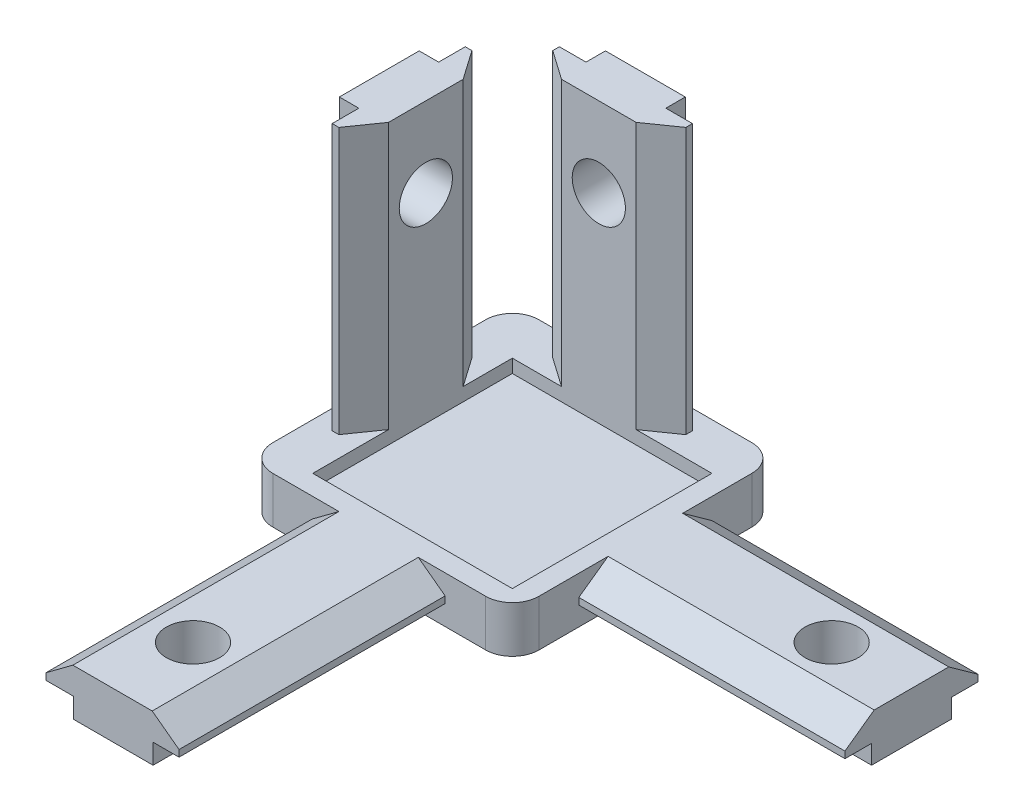
SolidWorks part; units mm, degrees
material "6063-T1"
ref_plane "Front Plane" through (0, 0, 0) normal (0, 0, 1) x (1, 0, 0)
ref_plane "Top Plane" through (0, 0, 0) normal (0, 1, 0) x (1, 0, 0)
ref_plane "Right Plane" through (0, 0, 0) normal (1, 0, 0) x (0, 0, -1)
sketch "Sketch1" plane through (0, 0, 0) normal (0, 1, 0) x (1, 0, 0)
  line L1 (8, -10) -> (-8, -10)
  line L2 (10, -8) -> (10, 8)
  line L3 (8, 10) -> (-8, 10)
  line L4 (-10, -8) -> (-10, 8)
  line L5 (10, -10) -> (-10, 10) construction
  line L6 (10, 10) -> (-10, -10) construction
  arc A0 (-10, -8) -> (-8, -10) centre (-8, -8) ccw
  arc A1 (8, -10) -> (10, -8) centre (8, -8) ccw
  arc A2 (10, 8) -> (8, 10) centre (8, 8) ccw
  arc A3 (-10, 8) -> (-8, 10) centre (-8, 8) cw
  point P0 (0, 0)
  dimension "D3" = 2
  dimension "D1" = 20
  dimension "D2" = 20
extrude "Boss-Extrude1" add sketch "Sketch1" along normal blind 3.5
sketch "Sketch2" plane through (0, 3.5, 0) normal (0, 1, 0) x (1, 0, 0)
  line L0 (-6.5, 6.5) -> (8.5, 6.5)
  line L1 (8.5, 6.5) -> (8.5, -8.5)
  line L2 (8.5, -8.5) -> (-6.5, -8.5)
  line L3 (-6.5, -8.5) -> (-6.5, 6.5)
  line L4 (-6.5, 2.965) -> (-10, 2.965) construction
  line L5 (-10, 8) -> (-10, -8) construction
  line L6 (1.2769, 6.5) -> (1.2769, 10) construction
  line L7 (8, 10) -> (-8, 10) construction
  dimension "D1" = 3.5
  dimension "D2" = 15
extrude "Cut-Extrude1" cut sketch "Sketch2" against normal blind 1
sketch "Sketch3" plane through (0, 3.5, 0) normal (0, 1, 0) x (1, 0, 0)
  line L0 (0, 10) -> (0, 6.5) construction
  line L1 (8, 10) -> (-8, 10) construction
  line L2 (8.5, 6.5) -> (-6.5, 6.5) construction
  line L3 (2.8032, 6.5) -> (-2.8032, 6.5)
  line L4 (8.5, 6.5) -> (-6.5, 6.5) construction
  line L5 (-2.8032, 6.5) -> (-5, 8.0375)
  line L7 (-3, 8.5375) -> (-3, 10)
  line L8 (-3, 10) -> (3, 10)
  line L9 (2.8032, 6.5) -> (5, 8.0375)
  line L11 (3, 8.5375) -> (3, 10)
  line L12 (-5, 8.0375) -> (-5, 8.5375)
  line L13 (-5, 8.5375) -> (-3, 8.5375)
  line L14 (5, 8.5375) -> (3, 8.5375)
  line L15 (5, 8.5375) -> (5, 8.0375)
  line L16 (-8.5375, 5) -> (-8.0375, 5)
  line L17 (-6.5, 2.8032) -> (-8.0375, 5)
  line L18 (-6.5, 2.8032) -> (-6.5, -2.8032)
  line L19 (-6.5, -2.8032) -> (-8.0375, -5)
  line L20 (-8.0375, -5) -> (-8.5375, -5)
  line L21 (-8.5375, -5) -> (-8.5375, -3)
  line L22 (-8.5375, -3) -> (-10, -3)
  line L23 (-10, -3) -> (-10, 3)
  line L24 (-8.5375, 3) -> (-10, 3)
  line L25 (-8.5375, 5) -> (-8.5375, 3)
  point P32 (0, 0)
  dimension "D1" = 3
  dimension "D2" = 10
  dimension "D3" = 0.5
  dimension "D4" = 2
extrude "Boss-Extrude2" add sketch "Sketch3" along normal blind 20
sketch "Sketch4" plane through (0, 0, 10) normal (0, 0, 1) x (1, 0, 0)
  line L0 (-8, 0) -> (8, 0) construction
  line L14 (2.9327, 3.5) -> (4.9508, 2)
  line L15 (4.9508, 1.5) -> (4.9508, 2)
  line L16 (4.9508, 1.5) -> (3, 1.5)
  line L17 (3, 1.5) -> (3, 0)
  line L18 (-3, 0) -> (3, 0)
  line L19 (-3, 1.5) -> (-3, 0)
  line L20 (-5.0492, 1.5) -> (-3, 1.5)
  line L21 (-5.0492, 2) -> (-5.0492, 1.5)
  line L22 (-3.0311, 3.5) -> (-5.0492, 2)
  line L23 (2.9327, 3.5) -> (-3.0311, 3.5)
  point P3 (0, 0)
  dimension "D1" = 10
  dimension "D2" = 6
  dimension "D3" = 3.5
  dimension "D4" = 1.5
  dimension "D5" = 0.5
extrude "Boss-Extrude3" add sketch "Sketch4" along normal blind 20
sketch "Sketch5" plane through (10, 0, 0) normal (1, 0, 0) x (0, 0, -1)
  line L0 (-8, 3.5) -> (8, 3.5) construction
  line L12 (2.8032, 3.5) -> (5, 1.9252)
  line L13 (5, 1.4252) -> (5, 1.9252)
  line L14 (5, 1.4252) -> (3, 1.4252)
  line L15 (3, 1.4252) -> (3, 0)
  line L16 (-3, 0) -> (3, 0)
  line L17 (-3, 1.4252) -> (-3, 0)
  line L18 (-5, 1.4252) -> (-3, 1.4252)
  line L19 (-5, 1.9252) -> (-5, 1.4252)
  line L20 (-2.8032, 3.5) -> (-5, 1.9252)
  line L21 (2.8032, 3.5) -> (-2.8032, 3.5)
  point P2 (0, 3.5)
  point P3 (0, 3.5)
  dimension "D1" = 10
  dimension "D2" = 1.4252
  dimension "D3" = 6
  dimension "D4" = 5.6065
  dimension "D5" = 3.5
extrude "Boss-Extrude4" add sketch "Sketch5" along normal blind 20
sketch "Sketch7" plane through (-10, 0, 0) normal (-1, 0, 0) x (0, 0, 1)
  line L0 (-3, 23.5) -> (3, 23.5) construction
  circle A0 centre (0, 17.5) radius 2
  dimension "D1" = 4
  dimension "D2" = 6
extrude "Cut-Extrude3" cut sketch "Sketch7" against normal blind 20
sketch "Sketch8" plane through (0, 0, -10) normal (0, 0, -1) x (-1, 0, 0)
  line L0 (-3, 23.5) -> (3, 23.5) construction
  circle A0 centre (0, 17.5) radius 2
  dimension "D1" = 4
  dimension "D2" = 6
extrude "Cut-Extrude4" cut sketch "Sketch8" against normal blind 20
sketch "Sketch9" plane through (0, 3.5, 0) normal (0, 1, 0) x (1, 0, 0)
  line L0 (2.9327, -30) -> (-3.0311, -30) construction
  circle A0 centre (0, -24) radius 2
  dimension "D1" = 4
  dimension "D2" = 6
extrude "Cut-Extrude5" cut sketch "Sketch9" against normal blind 20
sketch "Sketch10" plane through (0, 3.5, 0) normal (0, 1, 0) x (1, 0, 0)
  line L0 (30, 2.8032) -> (30, -2.8032) construction
  circle A0 centre (24, 0) radius 2
  dimension "D1" = 4
  dimension "D2" = 6
extrude "Cut-Extrude6" cut sketch "Sketch10" against normal blind 20
